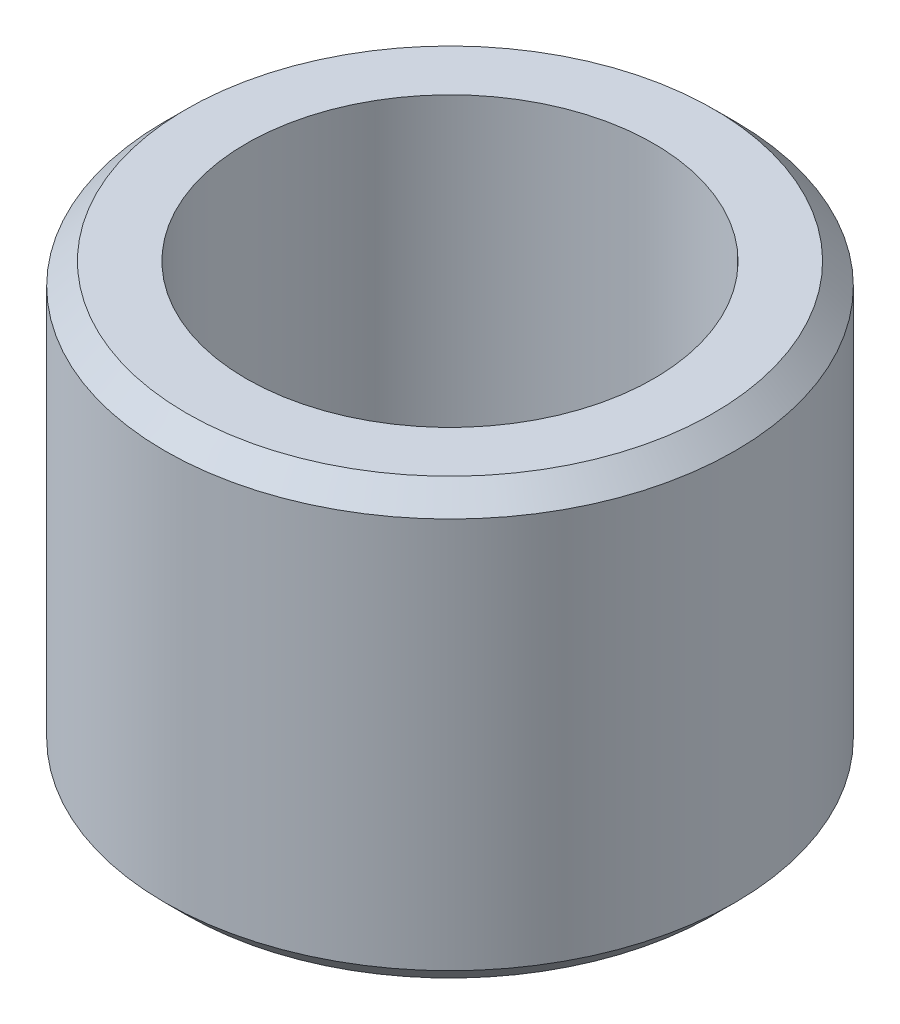
SolidWorks part; units mm, degrees
material "黄铜"
ref_plane "前视基准面" through (0, 0, 0) normal (0, 0, 1) x (1, 0, 0)
ref_plane "上视基准面" through (0, 0, 0) normal (0, 1, 0) x (1, 0, 0)
ref_plane "右视基准面" through (0, 0, 0) normal (1, 0, 0) x (0, 0, -1)
sketch "草图1" plane through (0, 0, 0) normal (0, 1, 0) x (1, 0, 0)
  circle A0 centre (0, 0) radius 7.5
  circle A1 centre (0, 0) radius 10.5
  dimension "D1" = 21
  dimension "D2" = 15
extrude "凸台-拉伸1" add sketch "草图1" along normal blind 16
chamfer "倒角1" distance 0.8 angle 45 2 edges at (0, 16, 10.5) (0, 0, 10.5)
